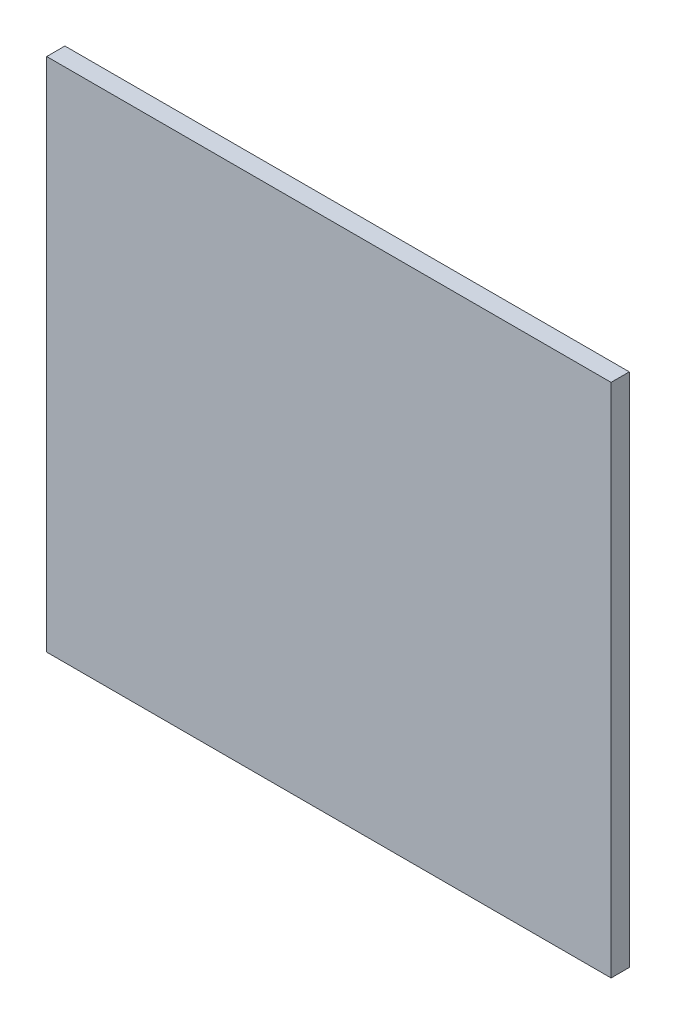
SolidWorks part; units mm, degrees
ref_plane "Plan de face" through (0, 0, 0) normal (0, 0, 1) x (1, 0, 0)
ref_plane "Plan de dessus" through (0, 0, 0) normal (0, 1, 0) x (1, 0, 0)
ref_plane "Plan de droite" through (0, 0, 0) normal (1, 0, 0) x (0, 0, -1)
sketch "Esquisse1" plane through (0, 0, 0) normal (0, 0, 1) x (1, 0, 0)
  line L1 (0, 0) -> (-186, 0)
  line L2 (0, 0) -> (0, 170)
  line L3 (0, 170) -> (-186, 170)
  line L4 (-186, 0) -> (-186, 170)
  dimension "D1" = 170
  dimension "D2" = 186
extrude "Boss.-Extru.1" add sketch "Esquisse1" along normal blind 6
